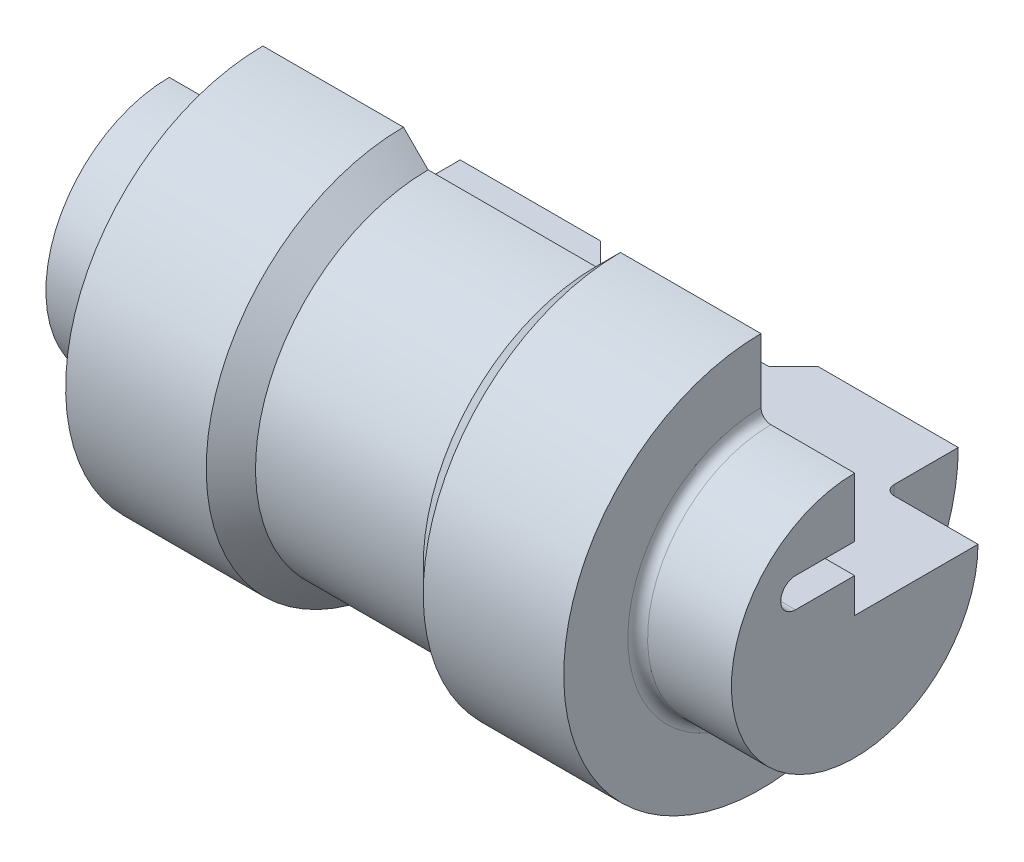
SolidWorks part; units mm, degrees
material "AISI 1020 Steel, Cold Rolled"
ref_plane "Front Plane" through (0, 0, 0) normal (0, 0, 1) x (1, 0, 0)
ref_plane "Top Plane" through (0, 0, 0) normal (0, 1, 0) x (1, 0, 0)
ref_plane "Right Plane" through (0, 0, 0) normal (1, 0, 0) x (0, 0, -1)
sketch "Sketch1" plane through (0, 0, 0) normal (0, 0, 1) x (1, 0, 0)
  line L0 (0, 0) -> (139, 0)
  line L1 (139, 0) -> (139, 25)
  line L2 (139, 25) -> (122, 25)
  line L3 (120, 27) -> (120, 40)
  line L4 (120, 40) -> (91.5, 40)
  line L5 (91.5, 40) -> (86.5, 35)
  line L6 (86.5, 35) -> (52.5, 35)
  line L7 (52.5, 35) -> (47.5, 40)
  line L8 (47.5, 40) -> (19, 40)
  line L9 (19, 40) -> (19, 27)
  line L10 (17, 25) -> (0, 25)
  line L11 (0, 25) -> (0, 0)
  arc A0 (120, 27) -> (122, 25) centre (122, 27) ccw
  arc A1 (19, 27) -> (17, 25) centre (17, 27) cw
  point P3 (89, 37.5)
  point P16 (120, 25)
  point P19 (19, 25)
  dimension "D12" = 2
  dimension "D13" = 2
  dimension "D1" = 25
  dimension "D2" = 25
  dimension "D3" = 139
  dimension "D4" = 40
  dimension "D5" = 19
  dimension "D6" = 19
  dimension "D7" = 28.5
  dimension "D8" = 28.5
  dimension "D9" = 45
  dimension "D10" = 2.5
  dimension "D11" = 34
revolve "Revolve2" add sketch "Sketch1" angle 270 about L0
sketch "Sketch2" plane through (139, 0, 0) normal (1, 0, 0) x (0, 0, -1)
  line L0 (0, 10) -> (-12, 10) construction
  line L1 (0, 0) -> (0, 25) construction
  line L2 (0, 7) -> (-12, 7)
  line L3 (0, 13) -> (-12, 13)
  line L4 (0, 13) -> (0, 7)
  line L5 (0, 0) -> (25, 0) construction
  line L6 (0, 27) -> (0, 40) construction
  arc A1 (-12, 13) -> (-12, 7) centre (-12, 10) ccw
  point P4 (-5.0889, 5.6361)
  dimension "D2" = 3
  dimension "D3" = 12
  dimension "D6" = 12
  dimension "D1" = 7
  dimension "D4" = 12
  dimension "D5" = 6
  dimension "D7" = 90
extrude "Cut-Extrude1" cut sketch "Sketch2" against normal through all
